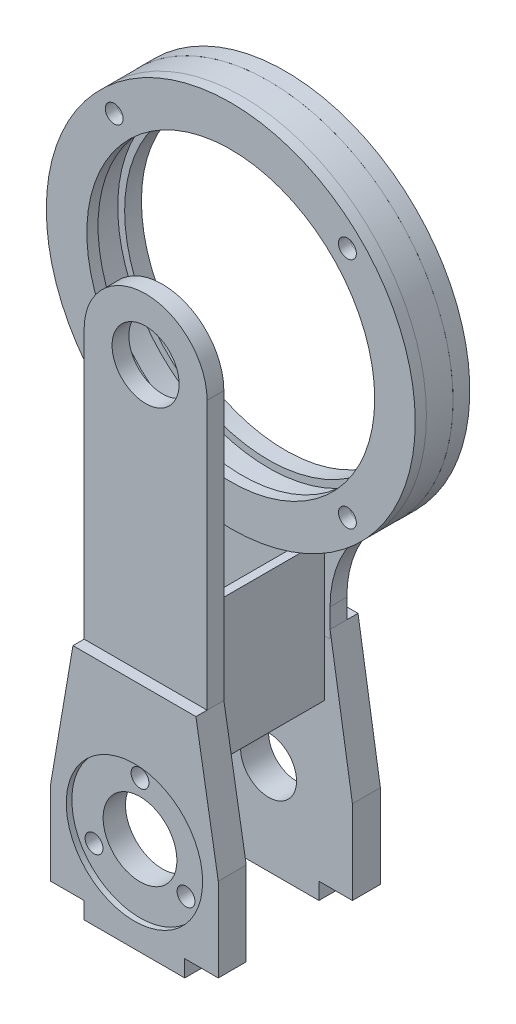
SolidWorks part; units mm, degrees
ref_plane "正面" through (0, 0, 0) normal (0, 0, 1) x (1, 0, 0)
ref_plane "平面" through (0, 0, 0) normal (0, 1, 0) x (1, 0, 0)
ref_plane "右側面" through (0, 0, 0) normal (1, 0, 0) x (0, 0, -1)
sketch "shoulder_roll_connection_sketch" plane through (0, 0, 0) normal (0, 1, 0) x (1, 0, 0)
  circle A0 centre (0, 0) radius 27.5 construction
  circle A1 centre (0, 0) radius 22.5 construction
  circle A2 centre (0, 22.5) radius 1.6 construction
  circle A3 centre (-22.5, 0) radius 1.6 construction
  circle A4 centre (22.5, 0) radius 1.6 construction
  circle A5 centre (0, -22.5) radius 1.6 construction
  dimension "D1" = 55
  dimension "D2" = 45
  dimension "D3" = 3.2
ref_plane "shoulder_yaw_m2006_mount_surface" through (0, 0, 9.5) normal (0, 0, 1) x (1, 0, 0)
ref_plane "shoulder_yaw_m2006_axis_hold_mount_surface" through (0, 0, -9.5) normal (0, 0, 1) x (1, 0, 0)
sketch "ｽｹｯﾁ4" plane through (0, 0, 9.5) normal (0, 0, 1) x (1, 0, 0)
  line L0 (-15, 0) -> (-9, 0)
  line L1 (-9, 0) -> (-9, -3)
  line L8 (-11, 38.5) -> (-15, 15)
  line L9 (-15, 15) -> (-15, 0)
  line L10 (0, 0) -> (0, 38.5) construction
  line L11 (-11, 38.5) -> (11, 38.5)
  line L12 (-9, -3) -> (9, -3)
  line L13 (15, 0) -> (9, 0)
  line L14 (15, 15) -> (15, 0)
  line L15 (11, 38.5) -> (15, 15)
  line L16 (9, 0) -> (9, -3)
  circle A0 centre (0, 13.5) radius 12.5 construction
  circle A1 centre (0, 13.5) radius 6.6
  circle A2 centre (0, 13.5) radius 9.5 construction
  circle A3 centre (0, 23) radius 1.6
  circle A5 centre (8.2272, 8.75) radius 1.6
  circle A6 centre (-8.2272, 8.75) radius 1.6
  point P15 (0, -3)
  point P22 (0, 13.5)
  dimension "D3" = 25
  dimension "D5" = 13.2
  dimension "D6" = 19
  dimension "D7" = 3
  dimension "D8" = 3.2
  dimension "D1" = 3
  dimension "D2" = 15
  dimension "D4" = 13.5
  dimension "D9" = 15
  dimension "D10" = 25
  dimension "D11" = 11
  dimension "D12" = 6
extrude "ﾎﾞｽ - 押し出し1" add sketch "ｽｹｯﾁ4" along normal blind 5
sketch "ｽｹｯﾁ7" plane through (0, 0, -9.5) normal (0, 0, 1) x (1, 0, 0)
  line L0 (15, 0) -> (9, 0)
  line L1 (9, 0) -> (9, -3)
  line L2 (9, -3) -> (-9, -3)
  line L3 (0, -3) -> (0, 40) construction
  line L4 (-11, 40) -> (11, 40)
  line L5 (11, 40) -> (15, 15)
  line L6 (15, 15) -> (15, 0)
  line L7 (30.25, 0) -> (-30.25, 0) construction
  line L8 (-15, 15) -> (-15, 0)
  line L9 (-11, 40) -> (-15, 15)
  line L10 (-9, 0) -> (-9, -3)
  line L11 (-15, 0) -> (-9, 0)
  circle A0 centre (0, 13.5) radius 5
  circle A1 centre (0, 13.5) radius 6.6 construction
  dimension "D7" = 10
  dimension "D1" = 11
  dimension "D2" = 15
  dimension "D3" = 3
  dimension "D4" = 6
  dimension "D5" = 30
  dimension "D6" = 40
extrude "ﾎﾞｽ - 押し出し2" add sketch "ｽｹｯﾁ7" against normal blind 5 separate body
sketch "ｽｹｯﾁ8" plane through (0, 38.5, 0) normal (0, 1, 0) x (1, 0, 0)
  line L0 (-8.5, -8.5) -> (8.5, -8.5)
  line L1 (-10, 10) -> (10, 10)
  line L2 (-10, 10) -> (-10, -10)
  line L3 (-10, -10) -> (10, -10)
  line L4 (10, 10) -> (10, -10)
  line L5 (-10, 10) -> (10, -10) construction
  line L6 (-10, -10) -> (10, 10) construction
  line L7 (8.5, 8.5) -> (8.5, -8.5)
  line L8 (-8.5, 8.5) -> (8.5, 8.5)
  line L9 (-8.5, 8.5) -> (-8.5, -8.5)
  point P0 (0, 0)
  dimension "D1" = 20
  dimension "D2" = 20
  dimension "D3" = 1.5
extrude "ﾎﾞｽ - 押し出し3" add sketch "ｽｹｯﾁ8" against normal blind 10 and the other way blind 15 separate body
sketch "ｽｹｯﾁ9" plane through (0, 0, -10) normal (0, 0, -1) x (-1, 0, 0)
  line L0 (-11, 38.5) -> (-11, 43.5116)
  line L1 (11, 38.5) -> (11, 43.5116)
  line L2 (0, 30.25) -> (0, -30.25) construction
  line L3 (-10, 53.5) -> (10, 53.5) construction
  line L4 (-10, 53.5) -> (-10, 28.5) construction
  line L5 (10, 53.5) -> (10, 28.5) construction
  line L6 (11, 38.5) -> (-11, 38.5)
  line L7 (-20.8597, 107.3597) -> (0, 86.5) construction
  line L8 (0, 86.5) -> (0, 119.5) construction
  arc A0 (19.3019, 59.7337) -> (-19.3019, 59.7337) centre (0, 86.5) ccw
  arc A1 (11, 43.5116) -> (19.3019, 59.7337) centre (31, 43.5116) cw
  arc A2 (-11, 43.5116) -> (-19.3019, 59.7337) centre (-31, 43.5116) ccw
  circle A3 centre (0, 86.5) radius 25.75
  circle A4 centre (0, 86.5) radius 29.5 construction
  circle A5 centre (-20.8597, 107.3597) radius 1.6
  circle A6 centre (20.8597, 107.3597) radius 1.6
  circle A7 centre (20.8597, 65.6403) radius 1.6
  circle A8 centre (-20.8597, 65.6403) radius 1.6
  point P22 (-52.6362, 91.6706)
  point P23 (0, 0)
  point P31 (0, 86.5)
  dimension "D1" = 66
  dimension "D5" = 20
  dimension "D6" = 51.5
  dimension "D7" = 59
  dimension "D8" = 45
  dimension "D9" = 3.2
  dimension "D2" = 1
  dimension "D3" = 1
  dimension "D4" = 15
  dimension "D10" = 4
extrude "ﾎﾞｽ - 押し出し4" add sketch "ｽｹｯﾁ9" along normal blind 2.5 and the other way blind 0.5 separate body
sketch "ｽｹｯﾁ10" plane through (0, 0, -9.5) normal (0, 0, 1) x (1, 0, 0)
  circle A0 centre (0, 86.5) radius 26.9875
  circle A1 centre (0, 86.5) radius 33
  arc A2 (19.3019, 59.7337) -> (-19.3019, 59.7337) centre (0, 86.5) ccw construction
  circle A3 centre (-20.8597, 65.6403) radius 1.6 construction
  circle A4 centre (20.8597, 65.6403) radius 1.6 construction
  circle A5 centre (20.8597, 107.3597) radius 1.6 construction
  circle A6 centre (-20.8597, 107.3597) radius 1.6 construction
  circle A7 centre (-20.8597, 65.6403) radius 1.6
  circle A8 centre (20.8597, 65.6403) radius 1.6
  circle A9 centre (20.8597, 107.3597) radius 1.6
  circle A10 centre (-20.8597, 107.3597) radius 1.6
  dimension "D1" = 53.975
extrude "ﾎﾞｽ - 押し出し5" add sketch "ｽｹｯﾁ10" along normal blind 4.763 separate body
sketch "ｽｹｯﾁ11" plane through (0, 0, -4.737) normal (0, 0, 1) x (1, 0, 0)
  circle A0 centre (0, 86.5) radius 33
  circle A1 centre (0, 86.5) radius 33 construction
  circle A2 centre (0, 86.5) radius 25.75 construction
  circle A3 centre (0, 86.5) radius 25.75
  circle A4 centre (20.8597, 65.6403) radius 1.6 construction
  circle A5 centre (-20.8597, 65.6403) radius 1.6 construction
  circle A6 centre (-20.8597, 107.3597) radius 1.6 construction
  circle A7 centre (20.8597, 107.3597) radius 1.6 construction
  circle A8 centre (20.8597, 65.6403) radius 1.6
  circle A9 centre (-20.8597, 65.6403) radius 1.6
  circle A10 centre (-20.8597, 107.3597) radius 1.6
  circle A11 centre (20.8597, 107.3597) radius 1.6
extrude "ﾎﾞｽ - 押し出し6" add sketch "ｽｹｯﾁ11" along normal blind 2 separate body
sketch "ｽｹｯﾁ12" plane through (0, 0, 14.5) normal (0, 0, 1) x (1, 0, 0)
  circle A0 centre (0, 13.5) radius 12.2
  dimension "D1" = 24.4
extrude "ｶｯﾄ - 押し出し1" cut sketch "ｽｹｯﾁ12" against normal blind 1
sketch "ｽｹｯﾁ13" plane through (0, 0, 10) normal (0, 0, 1) x (1, 0, 0)
  line L0 (-11, 38.5) -> (11, 38.5)
  line L1 (11, 38.5) -> (11, 86.5)
  line L2 (-11, 86.5) -> (-11, 38.5)
  line L4 (11, 38.5) -> (-11, 38.5) construction
  line L6 (-10, 53.5) -> (-10, 28.5) construction
  arc A0 (11, 86.5) -> (-11, 86.5) centre (0, 86.5) ccw
  circle A1 centre (0, 86.5) radius 25.75 construction
  circle A3 centre (0, 86.5) radius 6
  dimension "D1" = 12
  dimension "D2" = 1
extrude "ﾎﾞｽ - 押し出し7" add sketch "ｽｹｯﾁ13" along normal blind 2.5 and the other way blind 0.5 separate body
